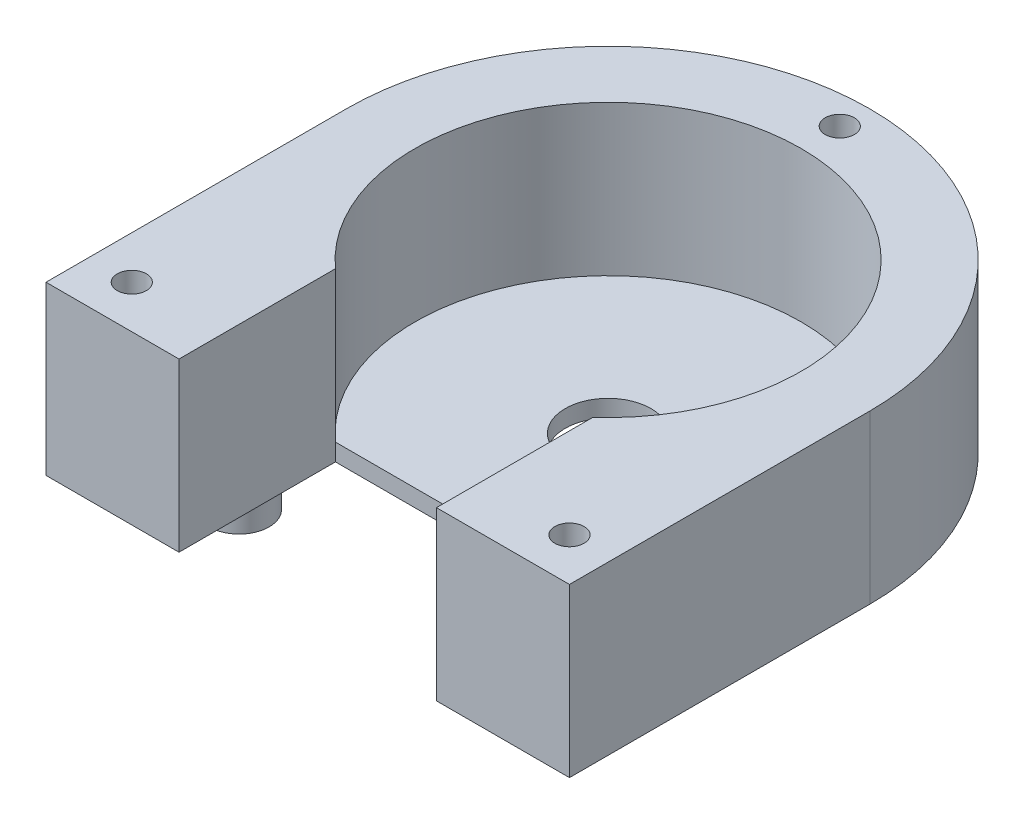
SolidWorks part; units mm, degrees
ref_plane "Front Plane" through (0, 0, 0) normal (0, 0, 1) x (1, 0, 0)
ref_plane "Top Plane" through (0, 0, 0) normal (0, 1, 0) x (1, 0, 0)
ref_plane "Right Plane" through (0, 0, 0) normal (1, 0, 0) x (0, 0, -1)
sketch "Sketch1" plane through (0, 0, 0) normal (0, 1, 0) x (1, 0, 0)
  line L0 (-15, -16.7705) -> (-15, -35)
  line L1 (15, -16.7705) -> (15, -35)
  line L2 (30.5, 0) -> (30.5, -35)
  line L3 (30.5, -35) -> (-30.5, -35)
  line L4 (-30.5, -35) -> (-30.5, 0)
  circle A0 centre (0, 0) radius 22.5
  circle A1 centre (0, 0) radius 30.5
  point P9 (0, 0)
  point P14 (15.0037, -26.5587)
  point P15 (0, 0)
  point P16 (15.1422, -35)
  point P17 (-14.9992, -35)
  dimension "D1" = 45
  dimension "D3" = 30
  dimension "D4" = 35
  dimension "D2" = 8
extrude "Boss-Extrude1" add sketch "Sketch1" against normal blind 17.5 contours L1 A1 L0 A0 | A1 L4 L3 L0 | A1 L1 L3 L2
sketch "Sketch2" plane through (0, -17.5, 0) normal (0, -1, 0) x (1, 0, 0)
  line L0 (-15, 16.7705) -> (15, 16.7705)
  line L6 (15, 35) -> (15, 16.7705)
  line L7 (-15, 16.7705) -> (-15, 35)
  line L8 (-15, 35) -> (-30.5, 35)
  line L9 (-30.5, 35) -> (-30.5, 0)
  line L10 (30.5, 0) -> (30.5, 35)
  line L11 (30.5, 35) -> (15, 35)
  line L12 (15, 35) -> (15, 16.7705)
  line L13 (-15, 16.7705) -> (-15, 35)
  line L14 (-15, 35) -> (-30.5, 35)
  line L15 (-30.5, 35) -> (-30.5, 0)
  line L16 (30.5, 0) -> (30.5, 35)
  line L17 (30.5, 35) -> (15, 35)
  circle A0 centre (0, 0) radius 5
  arc A5 (-15, 16.7705) -> (15, 16.7705) centre (0, 0) ccw
  arc A6 (-30.5, 0) -> (30.5, 0) centre (0, 0) ccw
  arc A7 (-15, 16.7705) -> (15, 16.7705) centre (0, 0) ccw
  arc A8 (-30.5, 0) -> (30.5, 0) centre (0, 0) ccw
  line M5 (15, 35) -> (15, 16.7705)
  arc M6 (15, 16.7705) -> (-15, 16.7705) centre (0, 0) cw
  line M7 (-15, 16.7705) -> (-15, 35)
  arc M8 (-30.5, 0) -> (30.5, 0) centre (0, 0) ccw
  line M9 (-15, 35) -> (-30.5, 35)
  line M10 (-30.5, 35) -> (-30.5, 0)
  line M11 (30.5, 0) -> (30.5, 35)
  line M12 (30.5, 35) -> (15, 35)
  dimension "D2" = 10
  dimension "D1" = 0
extrude "Boss-Extrude2" add sketch "Sketch2" along normal blind 2 contours L0 A0 M6 | M12 M5 M6 M7 M9 M10 M8 M11
sketch "Sketch3" plane through (0, -19.5, 0) normal (0, -1, 0) x (1, 0, 0)
  line L0 (0, -1000) -> (0, 49000) construction
  circle A0 centre (20, -15) radius 1.6
  circle A1 centre (20, -15) radius 3.5
  circle A2 centre (20, 23) radius 1.6
  circle A3 centre (20, 23) radius 3.5
  circle A4 centre (-20, 23) radius 3.5
  circle A5 centre (-20, 23) radius 1.6
  circle A6 centre (-20, -15) radius 3.5
  circle A7 centre (-20, -15) radius 1.6
  point P15 (-20, -15)
  line B0 (20.8689, 26.0686) -> (17.0463, 27.4934) construction
  line B1 (16, 29) -> (16, 34) construction
  line B2 (15, 35) -> (-15, 35) construction
  line B3 (-16, 34) -> (-16, 29) construction
  line B4 (-17.0463, 27.4934) -> (-20.8689, 26.0686) construction
  line B5 (-23, 23) -> (-23, -15) construction
  line B6 (-20, -18) -> (20, -18) construction
  line B7 (23, -15) -> (23, 23) construction
  circle B8 centre (-20, -15) radius 1.3 construction
  circle B9 centre (-20, 23) radius 1.3 construction
  circle B10 centre (20, 23) radius 1.3 construction
  circle B11 centre (20, -15) radius 1.3 construction
  arc B12 (23, 23) -> (20.8689, 26.0686) centre (19.7252, 23) ccw construction
  arc B13 (16, 29) -> (17.0463, 27.4934) centre (17.6078, 29) ccw construction
  arc B14 (16, 34) -> (15, 35) centre (15, 34) ccw construction
  arc B15 (-15, 35) -> (-16, 34) centre (-15, 34) ccw construction
  arc B16 (-17.0463, 27.4934) -> (-16, 29) centre (-17.6078, 29) ccw construction
  arc B17 (-20.8689, 26.0686) -> (-23, 23) centre (-19.7252, 23) ccw construction
  arc B18 (-23, -15) -> (-20, -18) centre (-20, -15) ccw construction
  arc B19 (20, -18) -> (23, -15) centre (20, -15) ccw construction
  dimension "D1" = 3.2
  dimension "D2" = 7
  dimension "D3" = 15
  dimension "D4" = 20
  dimension "D5" = 38
sketch_block_instance "Block1-1"
sketch_block "Block1"
other "AlignGroup1"
extrude "Boss-Extrude3" add sketch "Sketch3" along normal blind 4.2 contours A4 A5 | A3 A2 | A1 A0 | A6 A7
sketch "Sketch4" plane through (0, -19.5, 0) normal (0, -1, 0) x (1, 0, 0)
  line L0 (0, -1000) -> (0, 49000) construction
  point P0 (0, -27)
  point P1 (25.5, 30)
  point P3 (0, -25.9536)
  point P6 (0, 0)
  point P7 (-25.5, 30)
  dimension "D1" = 25.5
  dimension "D2" = 30
  dimension "D3" = 27
hole_wizard "CBORE for M3 SHCS1" positions "Sketch4" profile "Sketch5" counterbore size "M3" standard "ANSI Metric"
sketch "Sketch5" plane through (0, -19.5, -27) normal (1, 0, 0) x (0, 0, -1)
  line L0 (0, 0) -> (0, 20.5215)
  line L1 (0, 20.5215) -> (1.7, 19.5)
  line L2 (1.7, 19.5) -> (1.7, 3)
  line L3 (1.7, 3) -> (3.25, 3)
  line L4 (3.25, 3) -> (3.25, 0)
  line L5 (3.25, 0) -> (0, 0)
  line L10 (0, 20.5215) -> (-1.7, 19.5) construction
  line L11 (0, -6.35) -> (0, 107.95) construction
  dimension "Hole Dia." = 3.4
  dimension "Hole Depth" = 19.5
  dimension "C'Bore Dia." = 6.5
  dimension "C'Bore Depth" = 3
  dimension "Drill Angle" = 118
